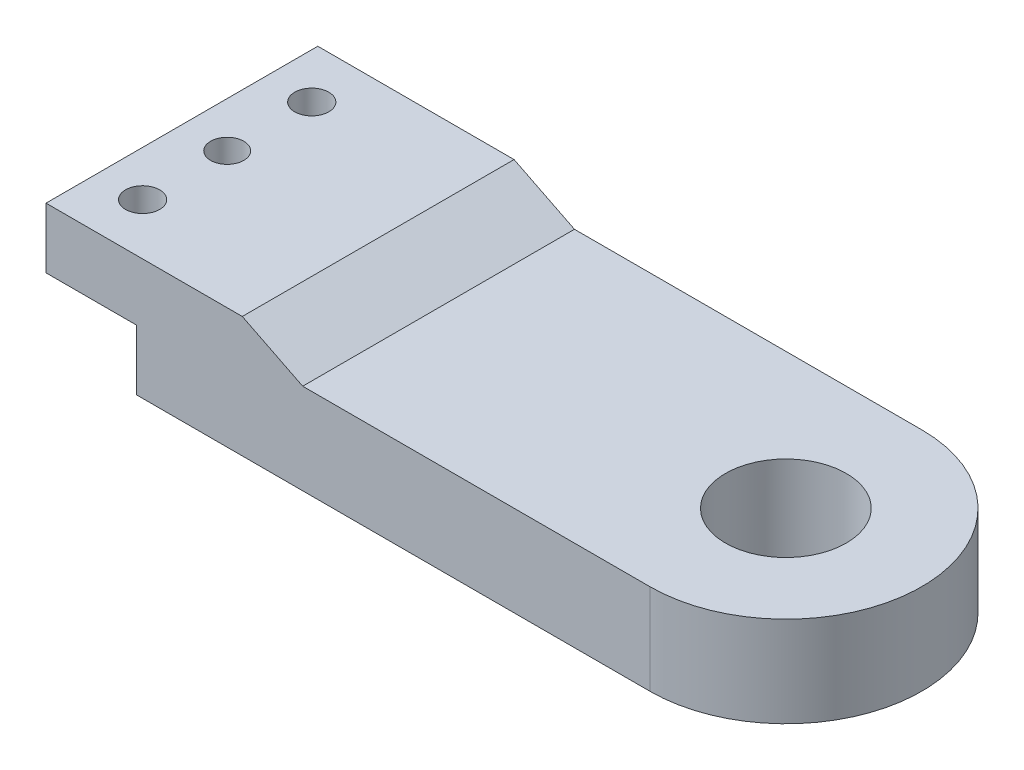
SolidWorks part; units mm, degrees
ref_plane "Front" through (0, 0, 0) normal (0, 0, 1) x (1, 0, 0)
ref_plane "Top" through (0, 0, 0) normal (0, 1, 0) x (1, 0, 0)
ref_plane "Right" through (0, 0, 0) normal (1, 0, 0) x (0, 0, -1)
sketch "草图1" plane through (0, 0, 0) normal (0, 1, 0) x (1, 0, 0)
  line L0 (-133.6287, 0) -> (76.3875, 0) construction
  line L2 (0, 22.5) -> (-100, 22.5)
  line L3 (0, 22.5) -> (0, -22.5) construction
  line L4 (0, -22.5) -> (-100, -22.5)
  line L5 (-100, 22.5) -> (-100, -22.5)
  arc A0 (0, 22.5) -> (0, -22.5) centre (0, 0) cw
  dimension "D1" = 22.5
  dimension "D2" = 100
extrude "凸台-拉伸1" add sketch "草图1" along normal blind 20
sketch "草图2" plane through (0, 0, 22.5) normal (0, 0, 1) x (1, 0, 0)
  line L1 (-100, 0) -> (-85, 0)
  line L2 (-100, 0) -> (-100, 10)
  line L3 (-100, 10) -> (-85, 10)
  line L4 (-85, 0) -> (-85, 10)
  dimension "D1" = 15
  dimension "D2" = 10
extrude "切除-拉伸1" cut sketch "草图2" against normal up to next
sketch "草图3" plane through (0, 10, 0) normal (0, -1, 0) x (1, 0, 0)
  line L0 (-92.5, 22.5) -> (-92.5, -22.5) construction
  line L1 (-85, 22.5) -> (-100, 22.5) construction
  line L2 (-100, -22.5) -> (-85, -22.5) construction
  line L3 (-100, 0) -> (-85, 0) construction
  line L4 (-100, -22.5) -> (-100, 22.5) construction
  line L5 (-85, -22.5) -> (-85, 22.5) construction
  circle A0 centre (-92.5, 0) radius 2.75
  circle A1 centre (-92.5, 14) radius 2.8241
  circle A2 centre (-92.5, -14) radius 2.8241
  dimension "D1" = 5.5
  dimension "D2" = 14
extrude "切除-拉伸2" cut sketch "草图3" against normal up to next
sketch "草图4" plane through (0, 0, 0) normal (0, 1, 0) x (1, 0, 0)
  circle A0 centre (0, 0) radius 10
  dimension "D1" = 20
extrude "切除-拉伸3" cut sketch "草图4" along normal up to next
sketch "草图5" plane through (0, 0, 22.5) normal (0, 0, 1) x (1, 0, 0)
  line L0 (22.5, 20) -> (22.5, 15)
  line L1 (22.5, 0) -> (22.5, 20) construction
  line L2 (22.5, 15) -> (-57.5, 15)
  line L3 (-57.5, 15) -> (-67.5, 20)
  line L4 (-100, 20) -> (0, 20) construction
  line L5 (-67.5, 20) -> (22.5, 20)
  dimension "D1" = 5
  dimension "D2" = 90
  dimension "D3" = 80
extrude "切除-拉伸4" cut sketch "草图5" against normal up to next
